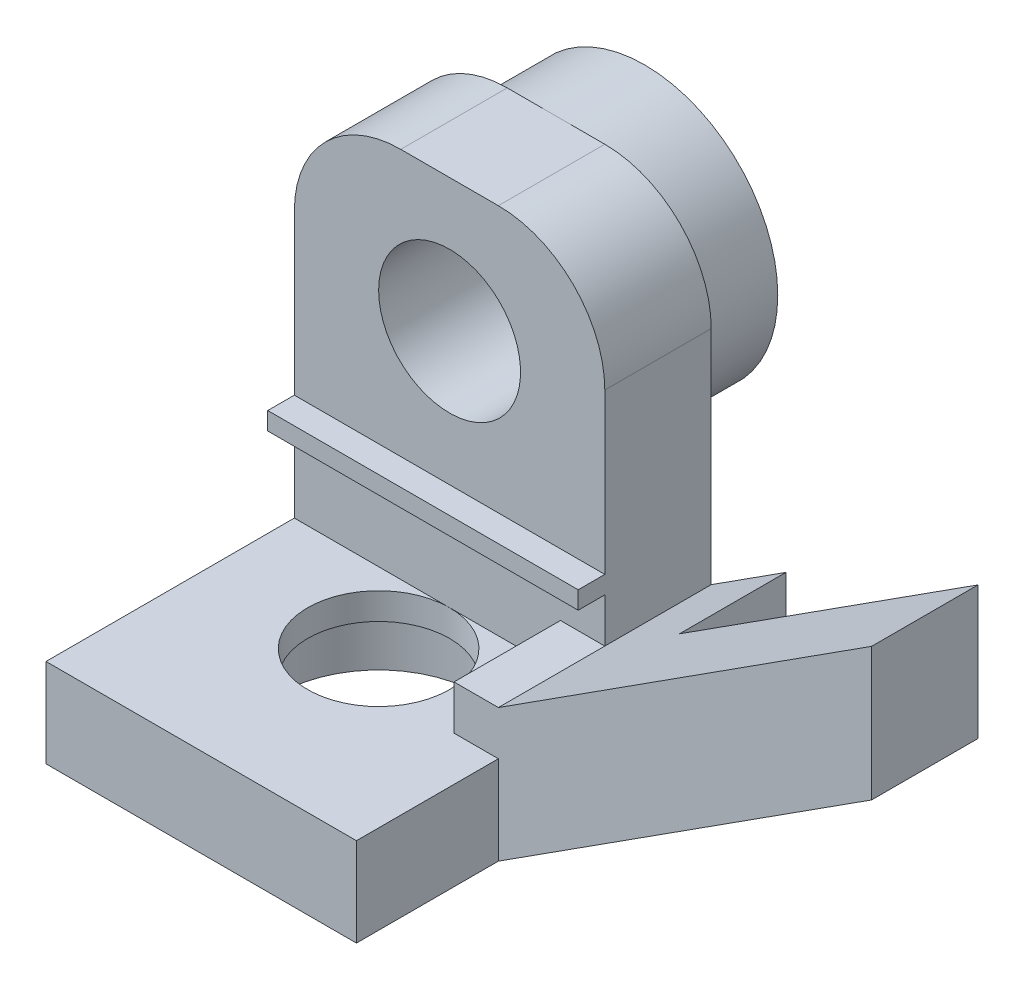
SolidWorks part; units mm, degrees
ref_plane "Front Plane" through (0, 0, 0) normal (0, 0, 1) x (1, 0, 0)
ref_plane "Top Plane" through (0, 0, 0) normal (0, 1, 0) x (1, 0, 0)
ref_plane "Right Plane" through (0, 0, 0) normal (1, 0, 0) x (0, 0, -1)
sketch "Sketch1" plane through (0, 0, 0) normal (0, 1, 0) x (1, 0, 0)
  line L1 (-17.5, 6) -> (17.5, 6)
  line L2 (-17.5, 6) -> (-17.5, -6)
  line L3 (-17.5, -6) -> (17.5, -6)
  line L4 (17.5, 6) -> (17.5, -6)
  line L5 (-17.5, 6) -> (17.5, -6) construction
  line L6 (-17.5, -6) -> (17.5, 6) construction
  point P0 (0, 0)
extrude "Boss-Extrude1" add sketch "Sketch1" along normal blind 20
sketch "Sketch2" plane through (0, 20, 0) normal (0, 1, 0) x (1, 0, 0)
  line L0 (17.5, -6) -> (17.5, 6) construction
  line L1 (-17.5, 6) -> (17.5, 6)
  line L2 (-17.5, 6) -> (-17.5, -6)
  line L3 (-17.5, -6) -> (17.5, -6)
  line L4 (17.5, 6) -> (17.5, -6)
  line L5 (-17.5, -6) -> (17.5, -6) construction
extrude "Boss-Extrude2" add sketch "Sketch2" along normal blind 10
sketch "Sketch4" plane through (0, 0, -6) normal (0, 0, -1) x (-1, 0, 0)
  line L0 (-17.5, 0) -> (-17.5, 15)
  line L1 (-17.5, 30) -> (-17.5, 0) construction
  line L2 (-17.5, 15) -> (17.5, 15)
  line L3 (17.5, 30) -> (17.5, 0) construction
  circle A0 centre (0, 15) radius 8
extrude "Cut-Extrude1" cut sketch "Sketch4" against normal blind 12 contours L2 A0 | L2 A0
fillet "Fillet1" radius 12 2 edges at (-17.5, 30, 0) (17.5, 30, 0)
sketch "Sketch5" plane through (0, 0, -6) normal (0, 0, -1) x (-1, 0, 0)
  circle A0 centre (0, 15) radius 12
  circle A1 centre (0, 15) radius 15
extrude "Boss-Extrude3" add sketch "Sketch5" along normal blind 10
sketch "Sketch6" plane through (0, 0, 0) normal (0, -1, 0) x (1, 0, 0)
  line L1 (-17.5, -6) -> (17.5, -6)
  line L2 (-17.5, -6) -> (-17.5, 9)
  line L3 (-17.5, 9) -> (17.5, 9)
  line L4 (17.5, -6) -> (17.5, 9)
extrude "Boss-Extrude4" add sketch "Sketch6" along normal blind 2
sketch "Sketch7" plane through (0, -2, 0) normal (0, -1, 0) x (1, 0, 0)
  line L1 (-17.5, -6) -> (17.5, -6)
  line L2 (-17.5, -6) -> (-17.5, 6)
  line L3 (-17.5, 6) -> (17.5, 6)
  line L4 (17.5, -6) -> (17.5, 6)
extrude "Boss-Extrude5" add sketch "Sketch7" along normal blind 10
sketch "Sketch8" plane through (0, -12, 0) normal (0, -1, 0) x (1, 0, 0)
  line L5 (-17.5, -6) -> (17.5, -6)
  line L6 (-17.5, -6) -> (-17.5, 34)
  line L7 (-17.5, 34) -> (17.5, 34)
  line L8 (17.5, -6) -> (17.5, 34)
extrude "Boss-Extrude6" add sketch "Sketch8" along normal blind 10
sketch "Sketch10" plane through (0, -22, 0) normal (0, -1, 0) x (1, 0, 0)
  circle A0 centre (0, 14) radius 11.2
extrude "Cut-Extrude2" cut sketch "Sketch10" against normal blind 7
sketch "Sketch11" plane through (0, -15, 0) normal (0, -1, 0) x (1, 0, 0)
  circle A0 centre (0, 14) radius 8
extrude "Cut-Extrude3" cut sketch "Sketch11" against normal blind 3
sketch "Sketch12" plane through (0, 0, -6) normal (0, 0, -1) x (-1, 0, 0)
  line L0 (-17.5, -22) -> (-25.9151, -16.5976)
  line L1 (-25.9151, -16.5976) -> (-25.9151, -1.5976)
  line L2 (-25.9151, -1.5976) -> (-17.5, -7)
  line L3 (-17.5, 18) -> (-17.5, -22) construction
  line L4 (-17.5, -7) -> (-17.5, -22)
extrude "Boss-Extrude7" add sketch "Sketch12" against normal blind 12
sketch "Sketch13" plane through (0, 0, 6) normal (0, 0, 1) x (1, 0, 0)
  line L0 (17.5, -22) -> (17.5, -7)
  line L5 (17.5, -7) -> (59.5755, 20.012)
  line L6 (17.5, -22) -> (59.5755, 5.012)
  line L7 (59.5755, 20.012) -> (59.5755, 5.012)
extrude "Boss-Extrude8" add sketch "Sketch13" along normal blind 12
sketch "Sketch14" plane through (17.5, 0, 0) normal (-1, 0, 0) x (0, 0, 1)
  line L0 (6, -12) -> (6, -2) construction
  line L1 (6, -7) -> (18, -7)
  line L2 (6, -7) -> (6, -12)
  line L3 (6, -12) -> (18, -12)
  line L4 (18, -7) -> (18, -12)
extrude "Boss-Extrude9" add sketch "Sketch14" along normal blind 5
